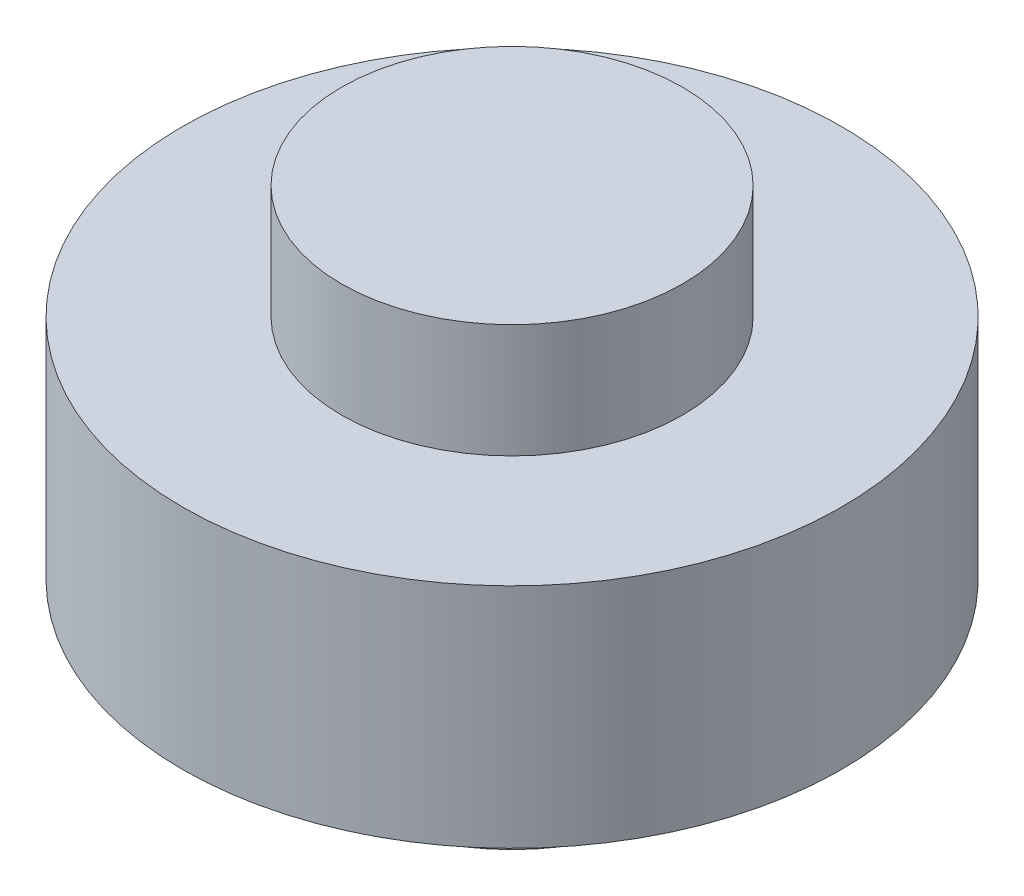
SolidWorks part; units mm, degrees
material "Plain Carbon Steel"
ref_plane "Front Plane" through (0, 0, 0) normal (0, 0, 1) x (1, 0, 0)
ref_plane "Top Plane" through (0, 0, 0) normal (0, 1, 0) x (1, 0, 0)
ref_plane "Right Plane" through (0, 0, 0) normal (1, 0, 0) x (0, 0, -1)
sketch "Sketch1" plane through (0, 0, 0) normal (0, 0, 1) x (1, 0, 0)
  line L0 (0, 101.6) -> (0, -101.6)
  line L1 (0, 101.6) -> (-76.2, 101.6)
  line L2 (-76.2, 101.6) -> (-76.2, 50.8)
  line L3 (-76.2, 50.8) -> (-147.32, 50.8)
  line L4 (-147.32, 50.8) -> (-147.32, -50.8)
  line L5 (-147.32, -50.8) -> (-76.2, -50.8)
  line L6 (-76.2, -50.8) -> (-76.2, -101.6)
  line L7 (-76.2, -101.6) -> (0, -101.6)
  point P7 (-76.2, 76.2)
  point P9 (-76.2, -76.2)
  point P10 (-38.1, 101.6)
  point P11 (-38.1, -101.6)
  point P13 (0, 0)
  dimension "D1" = 147.32
  dimension "D2" = 203.2
  dimension "D3" = 50.8
  dimension "D4" = 76.2
revolve "Revolve1" add sketch "Sketch1" angle 360 about L0
